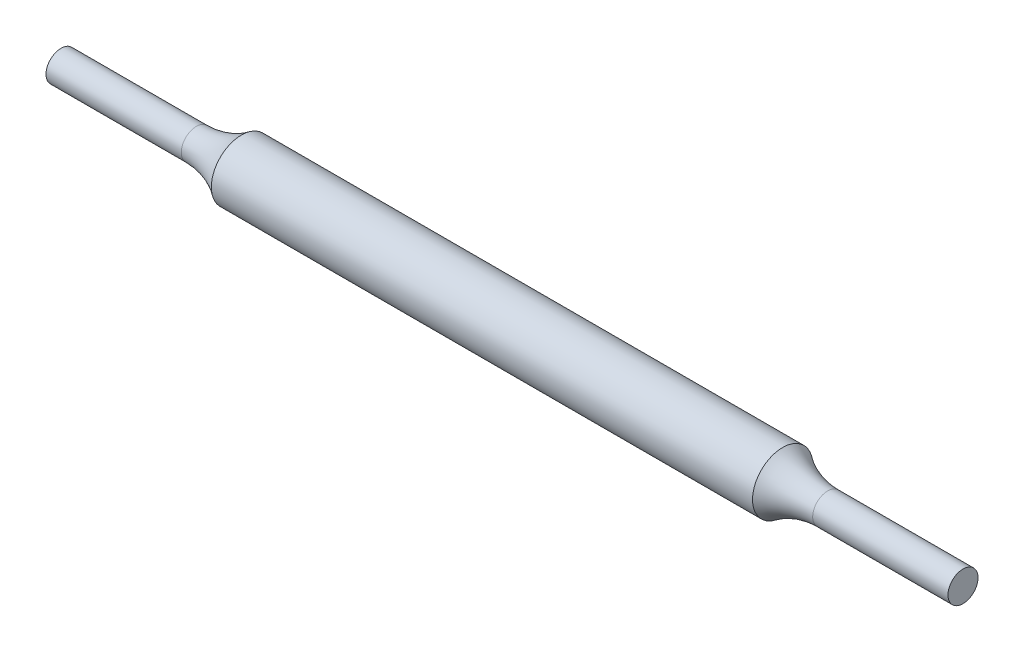
SolidWorks part; units mm, degrees
ref_plane "Front Plane" through (0, 0, 0) normal (0, 0, 1) x (1, 0, 0)
ref_plane "Top Plane" through (0, 0, 0) normal (0, 1, 0) x (1, 0, 0)
ref_plane "Right Plane" through (0, 0, 0) normal (1, 0, 0) x (0, 0, -1)
sketch "Sketch1" plane through (0, 0, 0) normal (0, 1, 0) x (1, 0, 0)
  line L2 (0, 0) -> (60, 0)
  line L3 (60, 0) -> (60, 1)
  line L4 (0, 0) -> (0, 1)
  line L5 (0, 1) -> (9, 1)
  line L6 (12, 2) -> (48, 2)
  line L7 (51, 1) -> (60, 1)
  arc A3 (9, 1) -> (12, 2) centre (9, 6) ccw
  arc A4 (51, 1) -> (48, 2) centre (51, 6) cw
  dimension "D2" = 3
  dimension "D3" = 60
  dimension "D8" = 3
  dimension "D1" = 1
  dimension "D4" = 2
  dimension "D5" = 36
  dimension "D7" = 9
revolve "Revolve1" add sketch "Sketch1" angle 360 about L2
